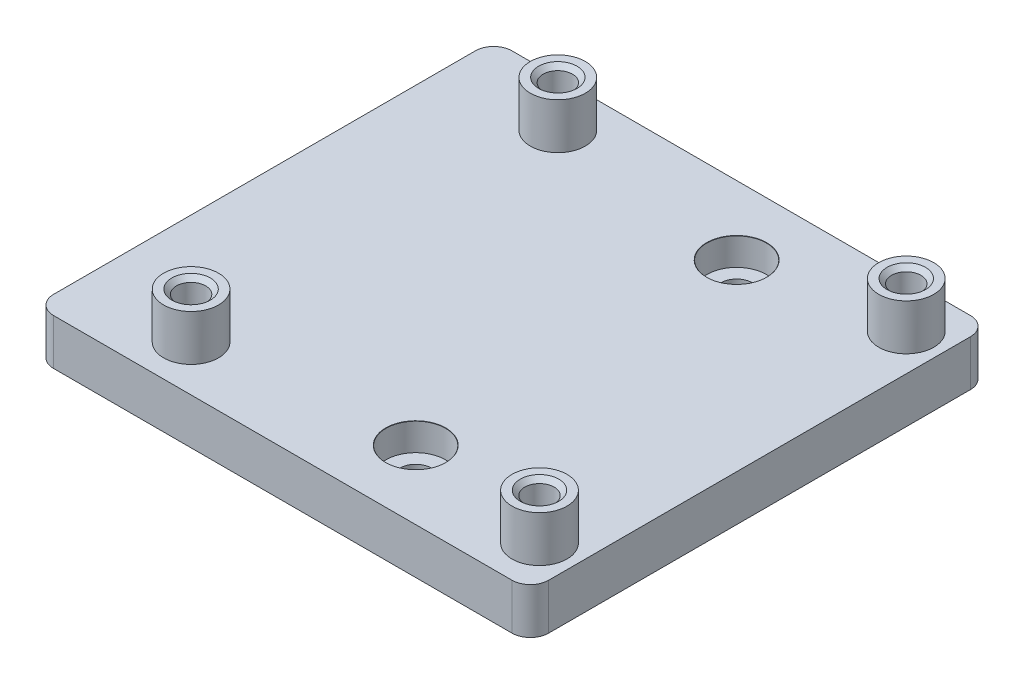
SolidWorks part; units mm, degrees
ref_plane "Front Plane" through (0, 0, 0) normal (0, 0, 1) x (1, 0, 0)
ref_plane "Top Plane" through (0, 0, 0) normal (0, 1, 0) x (1, 0, 0)
ref_plane "Right Plane" through (0, 0, 0) normal (1, 0, 0) x (0, 0, -1)
sketch "Sketch1" plane through (0, 0, 0) normal (0, 1, 0) x (1, 0, 0)
  line L1 (0, 0) -> (54, 0)
  line L2 (0, 0) -> (0, 50)
  line L3 (0, 50) -> (54, 50)
  line L4 (54, 0) -> (54, 50)
  dimension "D1" = 50
  dimension "D2" = 54
extrude "Boss-Extrude1" add sketch "Sketch1" along normal blind 5
sketch "Sketch2" plane through (0, 5, 0) normal (0, 1, 0) x (1, 0, 0)
  line L0 (54, 0) -> (54, 50) construction
  line L1 (12, 5) -> (50, 5) construction
  line L2 (12, 5) -> (12, 45) construction
  line L3 (12, 45) -> (50, 45) construction
  line L4 (50, 5) -> (50, 45) construction
  line L5 (12, 5) -> (50, 45) construction
  line L6 (12, 45) -> (50, 5) construction
  circle A0 centre (50, 5) radius 1.6
  circle A1 centre (50, 45) radius 1.6
  circle A2 centre (12, 45) radius 1.6
  circle A3 centre (12, 5) radius 1.6
  circle A4 centre (50, 5) radius 3
  circle A5 centre (50, 45) radius 3
  circle A6 centre (12, 45) radius 3
  circle A7 centre (12, 5) radius 3
  point P0 (31, 25)
  point P7 (54, 25)
  point P8 (50, 25)
  dimension "D4" = 3.2
  dimension "D5" = 6
  dimension "D1" = 40
  dimension "D2" = 38
  dimension "D3" = 4
extrude "Boss-Extrude2" add sketch "Sketch2" along normal blind 5
sketch "Sketch3" plane through (0, 5, 0) normal (0, 1, 0) x (1, 0, 0)
  line L0 (34, 42.5) -> (34, 7.5) construction
  line L1 (54, 0) -> (54, 50) construction
  point P0 (34, 42.5)
  point P1 (34, 7.5)
  point P6 (54, 25)
  point P7 (34, 25)
  dimension "D1" = 35
  dimension "D2" = 20
hole_wizard "CBORE for M3 SHCS1" positions "Sketch3" profile "Sketch4" counterbore size "M3" standard "ANSI Metric" end condition through all
sketch "Sketch4" plane through (34, 5, -42.5) normal (1, 0, 0) x (0, 0, 1)
  line L0 (0, 0) -> (0, 5)
  line L1 (0, 5) -> (1.7, 5)
  line L3 (1.7, 5) -> (1.7, 3)
  line L4 (3.25, 3) -> (1.7, 3)
  line L5 (3.25, 3) -> (3.25, 0.025)
  line L6 (3.25, 0.025) -> (3.275, 0)
  line L7 (3.275, 0) -> (0, 0)
  line L8 (-3.25, 0.025) -> (-3.275, 0) construction
  line L11 (0, -6.35) -> (0, 107.95) construction
  dimension "Thru Hole Dia." = 3.4
  dimension "Thru Hole Depth" = 5
  dimension "C'Bore Dia." = 6.5
  dimension "C'Bore Depth" = 3
  dimension "Near C'Sink Dia." = 6.55
  dimension "Near C'Sink Angle" = 90
chamfer "Chamfer1" distance 0.5 angle 45 4 edges at (12, 10, -3.4) (50, 10, -3.4) (50, 10, -43.4) (12, 10, -43.4)
fillet "Fillet1" radius 2 4 edges at (0, 2.5, -50) (54, 2.5, -50) (54, 2.5, 0) (0, 2.5, 0)
